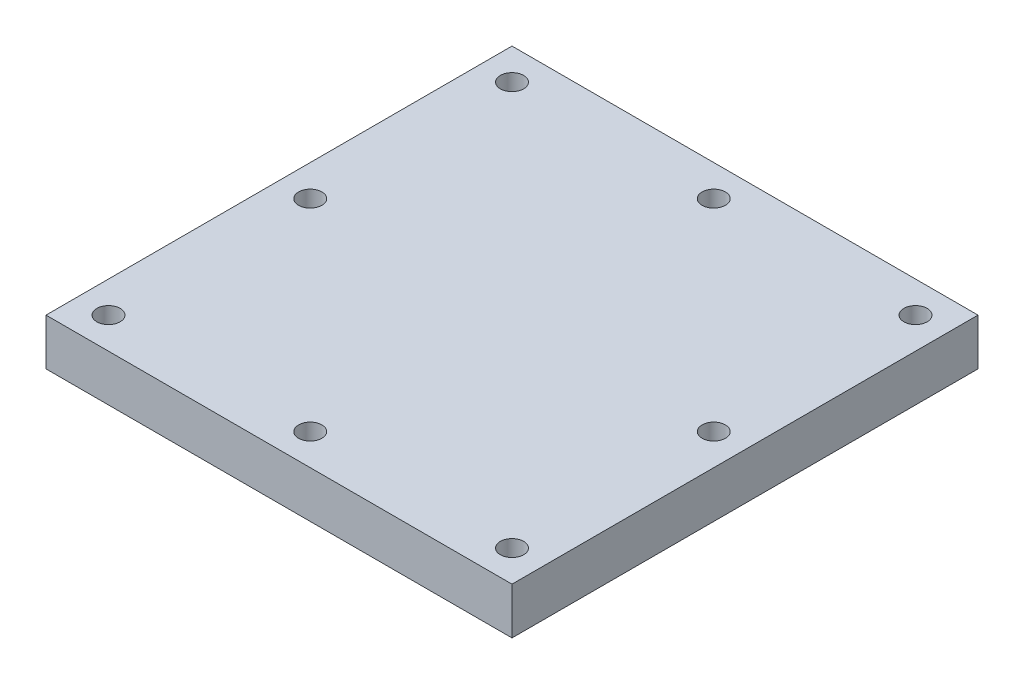
SolidWorks part; units mm, degrees
ref_plane "Front Plane" through (0, 0, 0) normal (0, 0, 1) x (1, 0, 0)
ref_plane "Top Plane" through (0, 0, 0) normal (0, 1, 0) x (1, 0, 0)
ref_plane "Right Plane" through (0, 0, 0) normal (1, 0, 0) x (0, 0, -1)
sketch "Sketch2" plane through (0, 0, 0) normal (0, 1, 0) x (1, 0, 0)
  line L0 (0, 0) -> (0, 500) construction
  line L1 (-500, -500) -> (500, -500)
  line L2 (-500, -500) -> (-500, 500)
  line L3 (-500, 500) -> (500, 500)
  line L4 (500, -500) -> (500, 500)
  line L5 (-500, -500) -> (500, 500) construction
  line L6 (-500, 500) -> (500, -500) construction
  line L7 (0, 500) -> (0, -500) construction
  line L8 (0, 0) -> (500, 0) construction
  line L9 (500, 0) -> (-500, 0) construction
  circle A0 centre (432.9515, 432.9515) radius 25
  circle A1 centre (-432.9515, 432.9515) radius 25
  circle A2 centre (-432.9515, -432.9515) radius 25
  circle A3 centre (432.9515, -432.9515) radius 25
  circle A4 centre (-432.9515, 0) radius 25
  circle A5 centre (432.9515, 0) radius 25
  circle A6 centre (0, 432.9515) radius 25
  circle A7 centre (0, -432.9515) radius 25
  point P0 (0, 0)
  dimension "D3" = 50
  dimension "D4" = 50
  dimension "D5" = 50
  dimension "D6" = 50
  dimension "D7" = 50
  dimension "D8" = 50
  dimension "D9" = 50
  dimension "D1" = 1000
  dimension "D2" = 1000
extrude "Boss-Extrude1" add sketch "Sketch2" along normal blind 100
